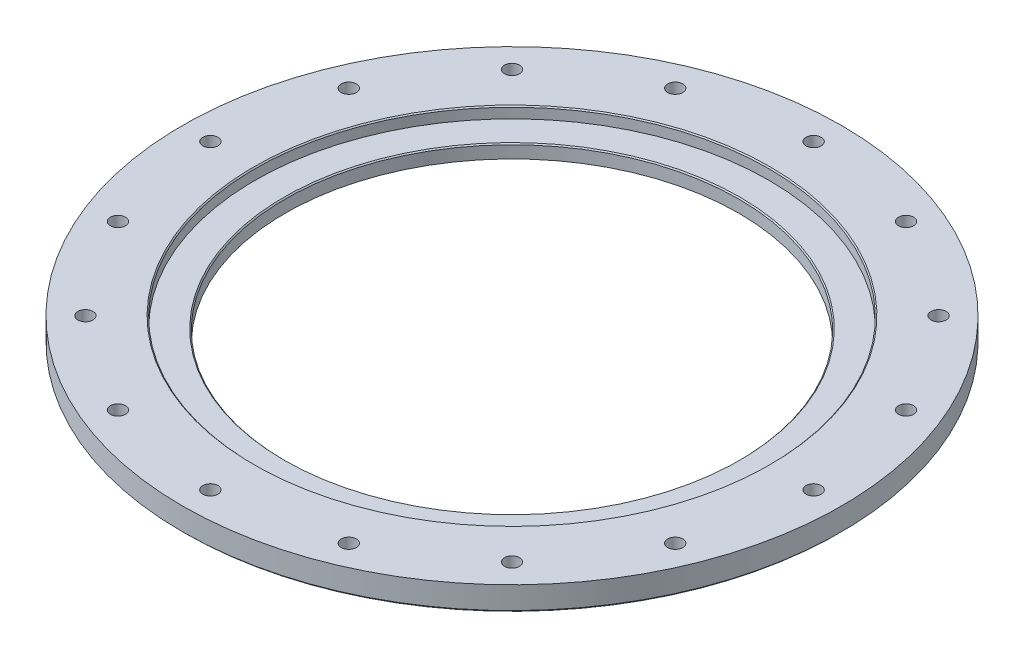
SolidWorks part; units mm, degrees
ref_plane "Front Plane" through (0, 0, 0) normal (0, 0, 1) x (1, 0, 0)
ref_plane "Top Plane" through (0, 0, 0) normal (0, 1, 0) x (1, 0, 0)
ref_plane "Right Plane" through (0, 0, 0) normal (1, 0, 0) x (0, 0, -1)
sketch "Sketch1" plane through (0, 0, 0) normal (0, 0, 1) x (1, 0, 0)
  line L0 (0, 0) -> (0, 139.5903) construction
  line L1 (-203, 0) -> (-295, 0)
  line L4 (-295, 0) -> (-295, 22)
  line L5 (-295, 22) -> (-230, 22)
  line L6 (-230, 22) -> (-230, 12)
  line L7 (-230, 12) -> (-203, 12)
  line L8 (-203, 12) -> (-203, 0)
  dimension "D1" = 460
  dimension "D2" = 406
  dimension "D3" = 12
  dimension "D4" = 10
  dimension "D5" = 590
revolve "Revolve1" add sketch "Sketch1" angle 360 about L0
sketch "Sketch2" plane through (0, 0, 0) normal (0, -1, 0) x (1, 0, 0)
  line L0 (0, 0) -> (0, 270) construction
  circle A0 centre (0, 0) radius 270 construction
  dimension "D1" = 540
hole_wizard "CBORE for M12 SHCS1" positions "Sketch3" profile "Sketch4" counterbore size "M12" standard "ANSI Metric" end condition through all
sketch "Sketch3" plane through (0, 0, 0) normal (0, -1, 0) x (-1, 0, 0)
  point P0 (0, -270)
sketch "Sketch4" plane through (0, 0, 270) normal (1, 0, 0) x (0, 0, -1)
  line L0 (0, 0) -> (0, 22)
  line L1 (0, 22) -> (6.75, 22)
  line L3 (6.75, 22) -> (6.75, 10)
  line L4 (10, 10) -> (6.75, 10)
  line L5 (10, 10) -> (10, 0.025)
  line L6 (10, 0.025) -> (10.025, 0)
  line L7 (10.025, 0) -> (0, 0)
  line L8 (-10, 0.025) -> (-10.025, 0) construction
  line L11 (0, -6.35) -> (0, 107.95) construction
  dimension "Thru Hole Dia." = 13.5
  dimension "Thru Hole Depth" = 22
  dimension "C'Bore Dia." = 20
  dimension "C'Bore Depth" = 10
  dimension "Near C'Sink Dia." = 20.05
  dimension "Near C'Sink Angle" = 90
pattern_circular "CirPattern1" count 16 over 360 about axis through (0, 0, 0) along (0, 1, 0) of "CBORE for M12 SHCS1"
chamfer "Chamfer1" distance 1 angle 45 2 edges at (0, 22, -230) (0, 12, -203)
chamfer "Chamfer2" distance 2 angle 45 1 edges at (0, 0, -295)
